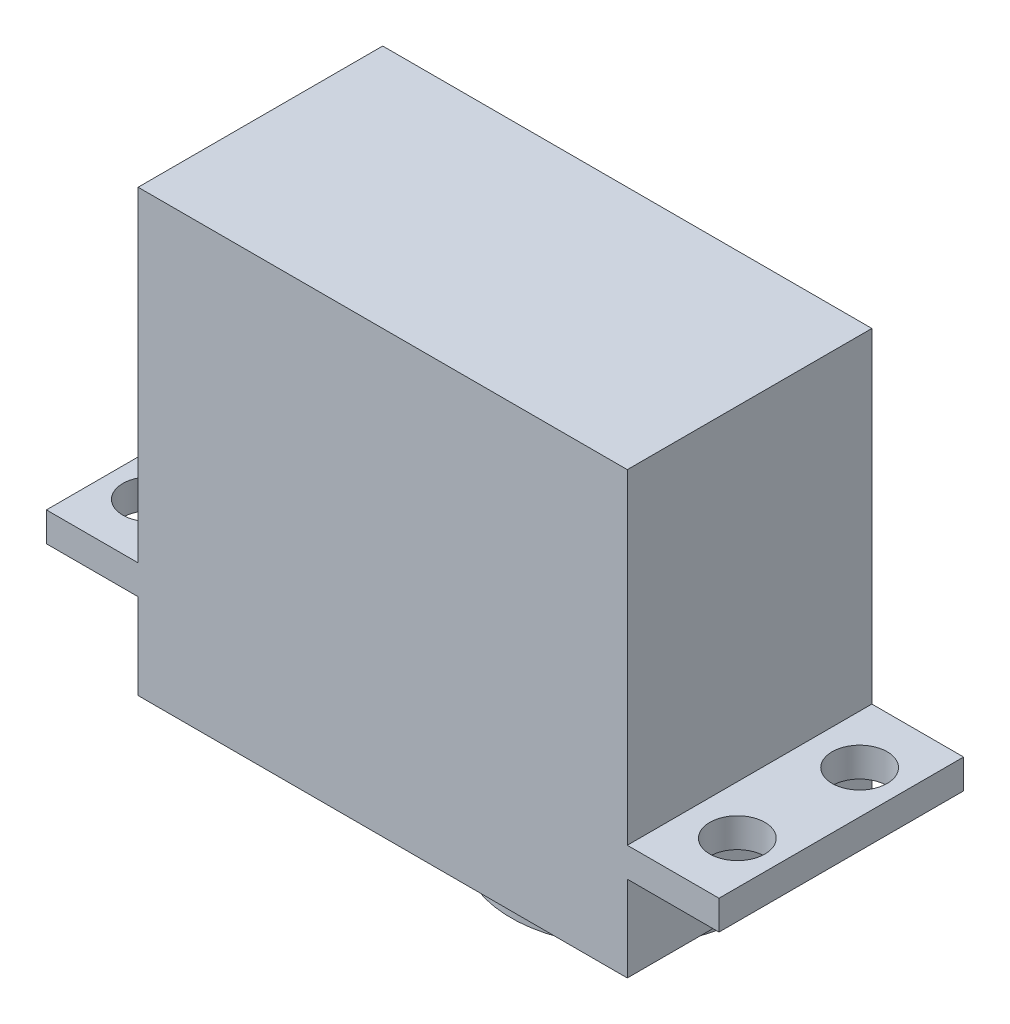
SolidWorks part; units mm, degrees
ref_plane "Front Plane" through (0, 0, 0) normal (0, 0, 1) x (1, 0, 0)
ref_plane "Top Plane" through (0, 0, 0) normal (0, 1, 0) x (1, 0, 0)
ref_plane "Right Plane" through (0, 0, 0) normal (1, 0, 0) x (0, 0, -1)
sketch "Sketch1" plane through (0, 0, 0) normal (0, 1, 0) x (1, 0, 0)
  line L1 (-20, -10) -> (20, -10)
  line L2 (-20, -10) -> (-20, 10)
  line L3 (-20, 10) -> (20, 10)
  line L4 (20, -10) -> (20, 10)
  line L5 (-20, -10) -> (20, 10) construction
  line L6 (-20, 10) -> (20, -10) construction
  point P0 (0, 0)
  dimension "D1" = 40
  dimension "D2" = 20
extrude "Boss-Extrude1" add sketch "Sketch1" along normal blind 36
ref_plane "Plane1" through (0, 7, 0) normal (0, 1, 0) x (1, 0, 0)
sketch "Sketch2" plane through (0, 7, 0) normal (0, 1, 0) x (1, 0, 0)
  line L0 (20, 10) -> (-20, 10) construction
  line L1 (-27.5, -10) -> (27.5, -10)
  line L2 (-27.5, -10) -> (-27.5, 10)
  line L3 (-27.5, 10) -> (27.5, 10)
  line L4 (27.5, -10) -> (27.5, 10)
  line L5 (-27.5, -10) -> (27.5, 10) construction
  line L6 (-27.5, 10) -> (27.5, -10) construction
  point P0 (0, 0)
  dimension "D1" = 55
extrude "Boss-Extrude2" add sketch "Sketch2" along normal blind 2.4
hole_wizard "M4 Clearance Hole1" positions "Sketch4" profile "Sketch3" hole size "M4" standard "ISO" end condition through all
sketch "Sketch4" plane through (0, 7, 0) normal (0, -1, 0) x (-1, 0, 0)
  line L0 (-24, 5) -> (-24, -5) construction
  line L1 (-24, -5) -> (-24, 0) construction
  line L2 (-24, 0) -> (0, 0) construction
  point P0 (-24, 5)
  point P2 (-24, -5)
  dimension "D1" = 24
  dimension "D2" = 10
sketch "Sketch3" plane through (24, 7, -5) normal (1, 0, 0) x (0, 0, -1)
  line L0 (0, 0) -> (0, 29)
  line L1 (0, 29) -> (2.25, 29)
  line L2 (2.25, 29) -> (2.25, 0)
  line L5 (2.25, 0) -> (0, 0)
  line L11 (0, -6.35) -> (0, 107.95) construction
  dimension "Thru Hole Dia." = 4.5
  dimension "Thru Hole Depth" = 29
mirror "Mirror1" about plane through (0, 0, 0) normal (1, 0, 0) of "M4 Clearance Hole1"
sketch "Sketch5" plane through (0, 0, 0) normal (0, -1, 0) x (1, 0, 0)
  line L0 (20, 10) -> (20, -10) construction
  circle A0 centre (10, 0) radius 9.5
  dimension "D1" = 10
  dimension "D2" = 19
extrude "Boss-Extrude3" add sketch "Sketch5" along normal blind 1
